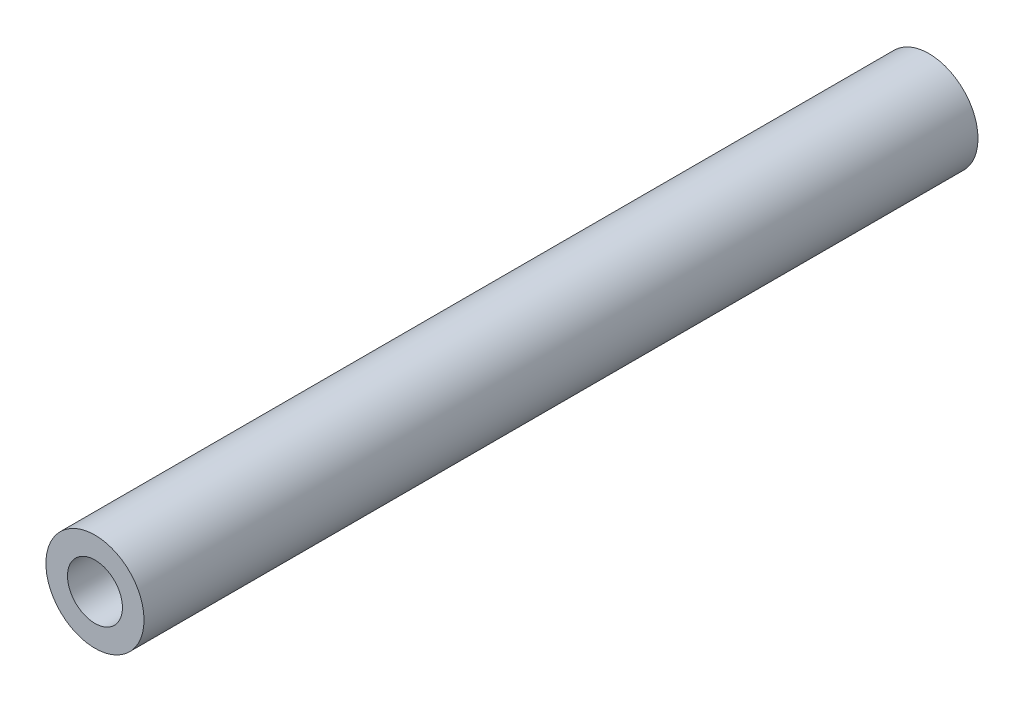
SolidWorks part; units mm, degrees
ref_plane "Front Plane" through (0, 0, 0) normal (0, 0, 1) x (1, 0, 0)
ref_plane "Top Plane" through (0, 0, 0) normal (0, 1, 0) x (1, 0, 0)
ref_plane "Right Plane" through (0, 0, 0) normal (1, 0, 0) x (0, 0, -1)
sketch "Sketch1" plane through (0, 0, 0) normal (0, 0, 1) x (1, 0, 0)
  circle A0 centre (0, 0) radius 3.175
  dimension "D1" = 6.35
extrude "Boss-Extrude1" add sketch "Sketch1" along normal blind 53.975
sketch "Sketch2" plane through (0, 0, 53.975) normal (0, 0, 1) x (1, 0, 0)
  circle A0 centre (0, 0) radius 1.778
  dimension "D1" = 3.556
extrude "Cut-Extrude1" cut sketch "Sketch2" against normal blind 53.975
